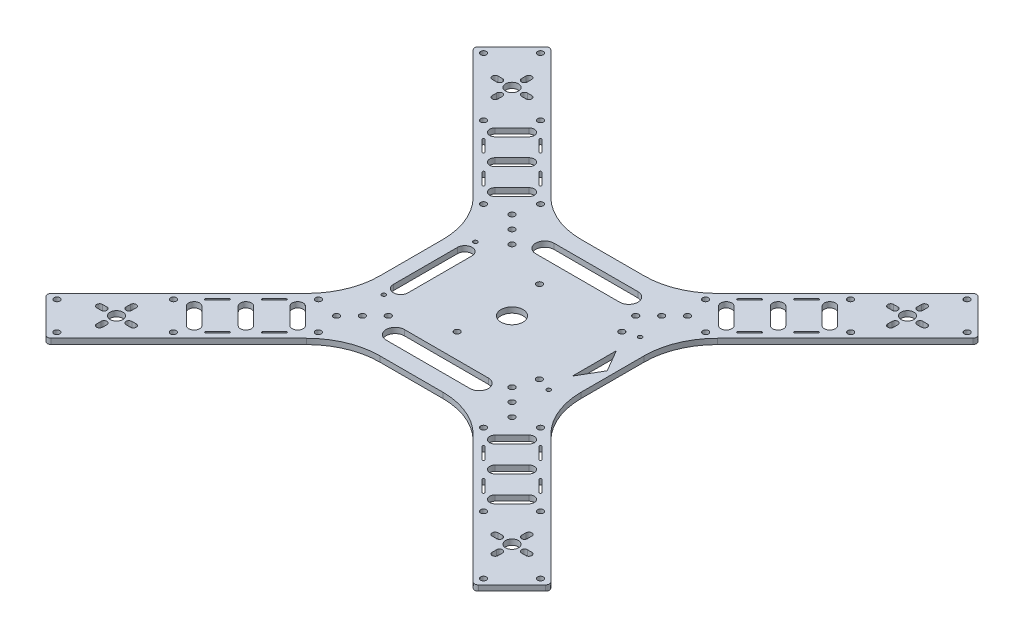
SolidWorks part; units mm, degrees
ref_plane "前视基准面" through (0, 0, 0) normal (0, 0, 1) x (1, 0, 0)
ref_plane "上视基准面" through (0, 0, 0) normal (0, 1, 0) x (1, 0, 0)
ref_plane "右视基准面" through (0, 0, 0) normal (1, 0, 0) x (0, 0, -1)
other "Configuration Table"
sketch "草图1" plane through (0, 0, 0) normal (0, 1, 0) x (1, 0, 0)
  line L0 (-17.2183, 55) -> (17.2183, 55)
  line L1 (-55, 17.2183) -> (-55, -17.2183)
  line L2 (55, 17.2183) -> (55, -17.2183)
  line L3 (-17.2183, -55) -> (17.2183, -55)
  line L4 (0, 55) -> (0, -55) construction
  line L5 (55, 55) -> (-55, -55) construction
  line L6 (45.5025, 66.7157) -> (116.6726, 137.8858)
  line L7 (-137.8858, -116.6726) -> (-116.6726, -137.8858)
  line L8 (116.6726, 137.8858) -> (137.8858, 116.6726)
  line L9 (66.7157, 45.5025) -> (137.8858, 116.6726)
  line L10 (55, 55) -> (108.033, 108.033) construction
  line L11 (55, 55) -> (58.5355, 58.5355)
  line L12 (-116.6726, 137.8858) -> (-45.5025, 66.7157)
  line L13 (-116.6726, 137.8858) -> (-137.8858, 116.6726)
  line L14 (-137.8858, 116.6726) -> (-66.7157, 45.5025)
  line L15 (137.8858, -116.6726) -> (116.6726, -137.8858)
  line L16 (66.7157, -45.5025) -> (137.8858, -116.6726)
  line L17 (116.6726, -137.8858) -> (45.5025, -66.7157)
  line L18 (-137.8858, -116.6726) -> (-66.7157, -45.5025)
  line L19 (-116.6726, -137.8858) -> (-45.5025, -66.7157)
  line L20 (68.0815, 77.2739) -> (77.2739, 68.0815) construction
  line L21 (53.9393, 63.1317) -> (63.1317, 53.9393) construction
  line L22 (70.2028, 79.3952) -> (79.3952, 70.2028)
  line L23 (56.0607, 65.253) -> (65.253, 56.0607)
  line L24 (51.818, 61.0104) -> (61.0104, 51.818)
  line L25 (65.9602, 75.1525) -> (75.1525, 65.9602)
  line L26 (82.2236, 91.416) -> (91.416, 82.2236) construction
  line L27 (84.3449, 93.5373) -> (93.5373, 84.3449)
  line L28 (80.1023, 89.2947) -> (89.2947, 80.1023)
  line L29 (45.1005, 60.6569) -> (84.6985, 100.2548) construction
  line L30 (45.1005, 60.6569) -> (60.6569, 45.1005) construction
  line L31 (84.6985, 100.2548) -> (100.2548, 84.6985) construction
  line L32 (60.6569, 45.1005) -> (100.2548, 84.6985) construction
  line L33 (45.1005, 60.6569) -> (100.2548, 84.6985) construction
  line L34 (84.6985, 100.2548) -> (60.6569, 45.1005) construction
  line L35 (68.0815, 77.2739) -> (77.2739, 68.0815)
  line L36 (108.033, 117.233) -> (108.033, 114.833) construction
  line L37 (117.233, 108.033) -> (114.833, 108.033) construction
  line L38 (109.633, 117.233) -> (109.633, 114.833)
  line L39 (106.433, 117.233) -> (106.433, 114.833)
  line L40 (117.233, 106.433) -> (114.833, 106.433)
  line L41 (117.233, 109.633) -> (114.833, 109.633)
  line L42 (108.033, 98.833) -> (108.033, 101.233) construction
  line L43 (106.433, 98.833) -> (106.433, 101.233)
  line L44 (109.633, 98.833) -> (109.633, 101.233)
  line L45 (98.833, 108.033) -> (101.233, 108.033) construction
  line L46 (98.833, 109.633) -> (101.233, 109.633)
  line L47 (98.833, 106.433) -> (101.233, 106.433)
  line L48 (55, -55) -> (58.5355, -58.5355)
  line L49 (77.2739, -68.0815) -> (68.0815, -77.2739)
  line L50 (55, -55) -> (108.033, -108.033) construction
  line L51 (60.6569, -45.1005) -> (100.2548, -84.6985) construction
  line L52 (60.6569, -45.1005) -> (45.1005, -60.6569) construction
  line L53 (100.2548, -84.6985) -> (84.6985, -100.2548) construction
  line L54 (45.1005, -60.6569) -> (84.6985, -100.2548) construction
  line L55 (60.6569, -45.1005) -> (84.6985, -100.2548) construction
  line L56 (100.2548, -84.6985) -> (45.1005, -60.6569) construction
  line L57 (63.1317, -53.9393) -> (53.9393, -63.1317) construction
  line L58 (65.253, -56.0607) -> (56.0607, -65.253)
  line L59 (61.0104, -51.818) -> (51.818, -61.0104)
  line L60 (77.2739, -68.0815) -> (68.0815, -77.2739) construction
  line L61 (79.3952, -70.2028) -> (70.2028, -79.3952)
  line L62 (75.1525, -65.9602) -> (65.9602, -75.1525)
  line L63 (91.416, -82.2236) -> (82.2236, -91.416) construction
  line L64 (93.5373, -84.3449) -> (84.3449, -93.5373)
  line L65 (89.2947, -80.1023) -> (80.1023, -89.2947)
  line L66 (117.233, -108.033) -> (114.833, -108.033) construction
  line L67 (117.233, -109.633) -> (114.833, -109.633)
  line L68 (117.233, -106.433) -> (114.833, -106.433)
  line L69 (108.033, -117.233) -> (108.033, -114.833) construction
  line L70 (106.433, -117.233) -> (106.433, -114.833)
  line L71 (109.633, -117.233) -> (109.633, -114.833)
  line L72 (98.833, -108.033) -> (101.233, -108.033) construction
  line L73 (98.833, -106.433) -> (101.233, -106.433)
  line L74 (98.833, -109.633) -> (101.233, -109.633)
  line L75 (108.033, -98.833) -> (108.033, -101.233) construction
  line L76 (109.633, -98.833) -> (109.633, -101.233)
  line L77 (106.433, -98.833) -> (106.433, -101.233)
  line L78 (-55, -55) -> (-58.5355, -58.5355)
  line L79 (-68.0815, -77.2739) -> (-77.2739, -68.0815)
  line L80 (-55, -55) -> (-108.033, -108.033) construction
  line L81 (-45.1005, -60.6569) -> (-84.6985, -100.2548) construction
  line L82 (-45.1005, -60.6569) -> (-60.6569, -45.1005) construction
  line L83 (-84.6985, -100.2548) -> (-100.2548, -84.6985) construction
  line L84 (-60.6569, -45.1005) -> (-100.2548, -84.6985) construction
  line L85 (-45.1005, -60.6569) -> (-100.2548, -84.6985) construction
  line L86 (-84.6985, -100.2548) -> (-60.6569, -45.1005) construction
  line L87 (-53.9393, -63.1317) -> (-63.1317, -53.9393) construction
  line L88 (-56.0607, -65.253) -> (-65.253, -56.0607)
  line L89 (-51.818, -61.0104) -> (-61.0104, -51.818)
  line L90 (-68.0815, -77.2739) -> (-77.2739, -68.0815) construction
  line L91 (-70.2028, -79.3952) -> (-79.3952, -70.2028)
  line L92 (-65.9602, -75.1525) -> (-75.1525, -65.9602)
  line L93 (-82.2236, -91.416) -> (-91.416, -82.2236) construction
  line L94 (-84.3449, -93.5373) -> (-93.5373, -84.3449)
  line L95 (-80.1023, -89.2947) -> (-89.2947, -80.1023)
  line L96 (-108.033, -117.233) -> (-108.033, -114.833) construction
  line L97 (-109.633, -117.233) -> (-109.633, -114.833)
  line L98 (-106.433, -117.233) -> (-106.433, -114.833)
  line L99 (-117.233, -108.033) -> (-114.833, -108.033) construction
  line L100 (-117.233, -106.433) -> (-114.833, -106.433)
  line L101 (-117.233, -109.633) -> (-114.833, -109.633)
  line L102 (-108.033, -98.833) -> (-108.033, -101.233) construction
  line L103 (-106.433, -98.833) -> (-106.433, -101.233)
  line L104 (-109.633, -98.833) -> (-109.633, -101.233)
  line L105 (-98.833, -108.033) -> (-101.233, -108.033) construction
  line L106 (-98.833, -109.633) -> (-101.233, -109.633)
  line L107 (-98.833, -106.433) -> (-101.233, -106.433)
  line L108 (-55, 55) -> (-58.5355, 58.5355)
  line L109 (-77.2739, 68.0815) -> (-68.0815, 77.2739)
  line L110 (-55, 55) -> (-108.033, 108.033) construction
  line L111 (-60.6569, 45.1005) -> (-100.2548, 84.6985) construction
  line L112 (-60.6569, 45.1005) -> (-45.1005, 60.6569) construction
  line L113 (-100.2548, 84.6985) -> (-84.6985, 100.2548) construction
  line L114 (-45.1005, 60.6569) -> (-84.6985, 100.2548) construction
  line L115 (-60.6569, 45.1005) -> (-84.6985, 100.2548) construction
  line L116 (-100.2548, 84.6985) -> (-45.1005, 60.6569) construction
  line L117 (-63.1317, 53.9393) -> (-53.9393, 63.1317) construction
  line L118 (-65.253, 56.0607) -> (-56.0607, 65.253)
  line L119 (-61.0104, 51.818) -> (-51.818, 61.0104)
  line L120 (-77.2739, 68.0815) -> (-68.0815, 77.2739) construction
  line L121 (-79.3952, 70.2028) -> (-70.2028, 79.3952)
  line L122 (-75.1525, 65.9602) -> (-65.9602, 75.1525)
  line L123 (-91.416, 82.2236) -> (-82.2236, 91.416) construction
  line L124 (-93.5373, 84.3449) -> (-84.3449, 93.5373)
  line L125 (-89.2947, 80.1023) -> (-80.1023, 89.2947)
  line L126 (-117.233, 108.033) -> (-114.833, 108.033) construction
  line L127 (-117.233, 109.633) -> (-114.833, 109.633)
  line L128 (-117.233, 106.433) -> (-114.833, 106.433)
  line L129 (-108.033, 117.233) -> (-108.033, 114.833) construction
  line L130 (-106.433, 117.233) -> (-106.433, 114.833)
  line L131 (-109.633, 117.233) -> (-109.633, 114.833)
  line L132 (-98.833, 108.033) -> (-101.233, 108.033) construction
  line L133 (-98.833, 106.433) -> (-101.233, 106.433)
  line L134 (-98.833, 109.633) -> (-101.233, 109.633)
  line L135 (-108.033, 98.833) -> (-108.033, 101.233) construction
  line L136 (-109.633, 98.833) -> (-109.633, 101.233)
  line L137 (-106.433, 98.833) -> (-106.433, 101.233)
  line L142 (-25.2933, 0) -> (25.2933, 0) construction
  line L143 (72.3283, 21.6796) -> (-80.2594, -24.0569) construction
  line L144 (-45, 25) -> (45, 25) construction
  line L145 (-45, 25) -> (-45, -25) construction
  line L146 (45, 25) -> (45, -25) construction
  line L147 (-45, -25) -> (45, -25) construction
  line L148 (-45, 25) -> (45, -25) construction
  line L149 (45, 25) -> (-45, -25) construction
  line L150 (55, 55) -> (47.9289, 47.9289)
  line L151 (-47.9289, 47.9289) -> (47.9289, 47.9289)
  line L152 (-40.8579, 40.8579) -> (40.8579, 40.8579)
  line L153 (-33.7868, 33.7868) -> (33.7868, 33.7868)
  line L154 (52, 0) -> (45, 0) construction
  line L155 (30, 47.9289) -> (47.9289, 47.9289) construction
  line L158 (30, 47.9289) -> (15.8579, 33.7868) construction
  line L159 (47.9289, 47.9289) -> (33.7868, 33.7868) construction
  line L160 (15.8579, 33.7868) -> (33.7868, 33.7868) construction
  line L161 (-22.9289, 40.8579) -> (22.9289, 40.8579) construction
  line L162 (-22.9289, 45.8579) -> (22.9289, 45.8579)
  line L163 (-22.9289, 35.8579) -> (22.9289, 35.8579)
  line L164 (45, 0) -> (45, 12)
  line L167 (45, 12) -> (52, 0)
  line L170 (-22.9289, -40.8579) -> (22.9289, -40.8579) construction
  line L171 (-22.9289, -45.8579) -> (22.9289, -45.8579)
  line L172 (-22.9289, -35.8579) -> (22.9289, -35.8579)
  line L173 (45, 0) -> (45, -12)
  line L176 (25.2933, 0) -> (52, 0) construction
  line L180 (-25.2933, 0) -> (-43.2933, 0)
  line L181 (-43.2933, 17.5) -> (-43.2933, -17.5) construction
  line L182 (69.4957, 53.9393) -> (75.8597, 60.3033) construction
  line L183 (-39.2933, 17.5) -> (-39.2933, -17.5)
  line L184 (-47.2933, 17.5) -> (-47.2933, -17.5)
  line L185 (85.052, 69.4957) -> (91.416, 75.8597) construction
  line L186 (69.1421, 54.2929) -> (75.5061, 60.6569)
  line L187 (69.8492, 53.5858) -> (76.2132, 59.9497)
  line L188 (84.6985, 69.8492) -> (91.0624, 76.2132)
  line L189 (85.4056, 69.1421) -> (91.7696, 75.5061)
  line L190 (53.9393, 69.4957) -> (60.3033, 75.8597) construction
  line L191 (54.2929, 69.1421) -> (60.6569, 75.5061)
  line L192 (53.5858, 69.8492) -> (59.9497, 76.2132)
  line L193 (69.4957, 85.052) -> (75.8597, 91.416) construction
  line L194 (69.8492, 84.6985) -> (76.2132, 91.0624)
  line L195 (69.1421, 85.4056) -> (75.5061, 91.7696)
  line L196 (53.9393, -69.4957) -> (60.3033, -75.8597) construction
  line L197 (54.2929, -69.1421) -> (60.6569, -75.5061)
  line L198 (53.5858, -69.8492) -> (59.9497, -76.2132)
  line L199 (69.4957, -85.052) -> (75.8597, -91.416) construction
  line L200 (69.8492, -84.6985) -> (76.2132, -91.0624)
  line L201 (69.1421, -85.4056) -> (75.5061, -91.7696)
  line L202 (69.4957, -53.9393) -> (75.8597, -60.3033) construction
  line L203 (69.1421, -54.2929) -> (75.5061, -60.6569)
  line L204 (69.8492, -53.5858) -> (76.2132, -59.9497)
  line L205 (85.052, -69.4957) -> (91.416, -75.8597) construction
  line L206 (84.6985, -69.8492) -> (91.0624, -76.2132)
  line L207 (85.4056, -69.1421) -> (91.7696, -75.5061)
  line L208 (-69.4957, -53.9393) -> (-75.8597, -60.3033) construction
  line L209 (-69.1421, -54.2929) -> (-75.5061, -60.6569)
  line L210 (-69.8492, -53.5858) -> (-76.2132, -59.9497)
  line L211 (-85.052, -69.4957) -> (-91.416, -75.8597) construction
  line L212 (-84.6985, -69.8492) -> (-91.0624, -76.2132)
  line L213 (-85.4056, -69.1421) -> (-91.7696, -75.5061)
  line L214 (-53.9393, -69.4957) -> (-60.3033, -75.8597) construction
  line L215 (-54.2929, -69.1421) -> (-60.6569, -75.5061)
  line L216 (-53.5858, -69.8492) -> (-59.9497, -76.2132)
  line L217 (-69.4957, -85.052) -> (-75.8597, -91.416) construction
  line L218 (-69.8492, -84.6985) -> (-76.2132, -91.0624)
  line L219 (-69.1421, -85.4056) -> (-75.5061, -91.7696)
  line L220 (-53.9393, 69.4957) -> (-60.3033, 75.8597) construction
  line L221 (-54.2929, 69.1421) -> (-60.6569, 75.5061)
  line L222 (-53.5858, 69.8492) -> (-59.9497, 76.2132)
  line L223 (-69.4957, 85.052) -> (-75.8597, 91.416) construction
  line L224 (-69.8492, 84.6985) -> (-76.2132, 91.0624)
  line L225 (-69.1421, 85.4056) -> (-75.5061, 91.7696)
  line L226 (-69.4957, 53.9393) -> (-75.8597, 60.3033) construction
  line L227 (-69.1421, 54.2929) -> (-75.5061, 60.6569)
  line L228 (-69.8492, 53.5858) -> (-76.2132, 59.9497)
  line L229 (-85.052, 69.4957) -> (-91.416, 75.8597) construction
  line L230 (-84.6985, 69.8492) -> (-91.0624, 76.2132)
  line L231 (-85.4056, 69.1421) -> (-91.7696, 75.5061)
  line L232 (45, -12) -> (52, 0)
  line L233 (0, 0) -> (15, 0)
  line L234 (-7.5, 22.5) -> (37.5, 22.5) construction
  line L235 (-7.5, 22.5) -> (-7.5, -22.5) construction
  line L236 (37.5, 22.5) -> (37.5, -22.5) construction
  line L237 (-7.5, -22.5) -> (37.5, -22.5) construction
  line L238 (-7.5, 22.5) -> (37.5, -22.5) construction
  line L239 (37.5, 22.5) -> (-7.5, -22.5) construction
  arc A0 (-55, 17.2183) -> (-66.7157, 45.5025) centre (-95, 17.2183) ccw
  arc A1 (55, 17.2183) -> (66.7157, 45.5025) centre (95, 17.2183) cw
  arc A2 (45.5025, 66.7157) -> (17.2183, 55) centre (17.2183, 95) cw
  arc A3 (-17.2183, 55) -> (-45.5025, 66.7157) centre (-17.2183, 95) cw
  arc A4 (66.7157, -45.5025) -> (55, -17.2183) centre (95, -17.2183) cw
  arc A5 (17.2183, -55) -> (45.5025, -66.7157) centre (17.2183, -95) cw
  arc A6 (-17.2183, -55) -> (-45.5025, -66.7157) centre (-17.2183, -95) ccw
  arc A7 (-66.7157, -45.5025) -> (-55, -17.2183) centre (-95, -17.2183) ccw
  circle A8 centre (108.033, 108.033) radius 14 construction
  circle A9 centre (108.033, 108.033) radius 8 construction
  circle A12 centre (116.033, 108.033) radius 1.6 construction
  circle A13 centre (108.033, 100.033) radius 1.6 construction
  circle A14 centre (100.033, 108.033) radius 1.6 construction
  circle A15 centre (108.033, 116.033) radius 1.6 construction
  arc A16 (56.0607, 65.253) -> (51.818, 61.0104) centre (53.9393, 63.1317) ccw
  arc A17 (61.0104, 51.818) -> (65.253, 56.0607) centre (63.1317, 53.9393) ccw
  arc A18 (70.2028, 79.3952) -> (65.9602, 75.1525) centre (68.0815, 77.2739) ccw
  arc A19 (75.1525, 65.9602) -> (79.3952, 70.2028) centre (77.2739, 68.0815) ccw
  arc A20 (84.3449, 93.5373) -> (80.1023, 89.2947) centre (82.2236, 91.416) ccw
  arc A21 (89.2947, 80.1023) -> (93.5373, 84.3449) centre (91.416, 82.2236) ccw
  circle A22 centre (84.6985, 100.2548) radius 1.6
  circle A23 centre (100.2548, 84.6985) radius 1.6
  circle A24 centre (60.6569, 45.1005) radius 1.6
  circle A25 centre (45.1005, 60.6569) radius 1.6
  circle A26 centre (108.033, 108.033) radius 3.5
  arc A27 (109.633, 117.233) -> (106.433, 117.233) centre (108.033, 117.233) ccw
  arc A28 (106.433, 114.833) -> (109.633, 114.833) centre (108.033, 114.833) ccw
  arc A29 (117.233, 106.433) -> (117.233, 109.633) centre (117.233, 108.033) ccw
  arc A30 (114.833, 109.633) -> (114.833, 106.433) centre (114.833, 108.033) ccw
  arc A31 (106.433, 98.833) -> (109.633, 98.833) centre (108.033, 98.833) ccw
  arc A32 (109.633, 101.233) -> (106.433, 101.233) centre (108.033, 101.233) ccw
  arc A33 (98.833, 109.633) -> (98.833, 106.433) centre (98.833, 108.033) ccw
  arc A34 (101.233, 106.433) -> (101.233, 109.633) centre (101.233, 108.033) ccw
  circle A35 centre (116.5183, 132.0746) radius 1.6
  circle A36 centre (132.0746, 116.5183) radius 1.6
  circle A37 centre (100.2548, -84.6985) radius 1.6
  circle A38 centre (84.6985, -100.2548) radius 1.6
  circle A39 centre (45.1005, -60.6569) radius 1.6
  circle A40 centre (60.6569, -45.1005) radius 1.6
  circle A41 centre (108.033, -108.033) radius 3.5
  circle A42 centre (132.0746, -116.5183) radius 1.6
  circle A43 centre (116.5183, -132.0746) radius 1.6
  circle A44 centre (108.033, -108.033) radius 14 construction
  circle A45 centre (108.033, -108.033) radius 8 construction
  circle A46 centre (108.033, -116.033) radius 1.6 construction
  circle A47 centre (100.033, -108.033) radius 1.6 construction
  circle A48 centre (108.033, -100.033) radius 1.6 construction
  circle A49 centre (116.033, -108.033) radius 1.6 construction
  arc A50 (65.253, -56.0607) -> (61.0104, -51.818) centre (63.1317, -53.9393) ccw
  arc A51 (51.818, -61.0104) -> (56.0607, -65.253) centre (53.9393, -63.1317) ccw
  arc A52 (79.3952, -70.2028) -> (75.1525, -65.9602) centre (77.2739, -68.0815) ccw
  arc A53 (65.9602, -75.1525) -> (70.2028, -79.3952) centre (68.0815, -77.2739) ccw
  arc A54 (93.5373, -84.3449) -> (89.2947, -80.1023) centre (91.416, -82.2236) ccw
  arc A55 (80.1023, -89.2947) -> (84.3449, -93.5373) centre (82.2236, -91.416) ccw
  arc A56 (117.233, -109.633) -> (117.233, -106.433) centre (117.233, -108.033) ccw
  arc A57 (114.833, -106.433) -> (114.833, -109.633) centre (114.833, -108.033) ccw
  arc A58 (106.433, -117.233) -> (109.633, -117.233) centre (108.033, -117.233) ccw
  arc A59 (109.633, -114.833) -> (106.433, -114.833) centre (108.033, -114.833) ccw
  arc A60 (98.833, -106.433) -> (98.833, -109.633) centre (98.833, -108.033) ccw
  arc A61 (101.233, -109.633) -> (101.233, -106.433) centre (101.233, -108.033) ccw
  arc A62 (109.633, -98.833) -> (106.433, -98.833) centre (108.033, -98.833) ccw
  arc A63 (106.433, -101.233) -> (109.633, -101.233) centre (108.033, -101.233) ccw
  circle A64 centre (-84.6985, -100.2548) radius 1.6
  circle A65 centre (-100.2548, -84.6985) radius 1.6
  circle A66 centre (-60.6569, -45.1005) radius 1.6
  circle A67 centre (-45.1005, -60.6569) radius 1.6
  circle A68 centre (-108.033, -108.033) radius 3.5
  circle A69 centre (-116.5183, -132.0746) radius 1.6
  circle A70 centre (-132.0746, -116.5183) radius 1.6
  circle A71 centre (-108.033, -108.033) radius 14 construction
  circle A72 centre (-108.033, -108.033) radius 8 construction
  circle A73 centre (-116.033, -108.033) radius 1.6 construction
  circle A74 centre (-108.033, -100.033) radius 1.6 construction
  circle A75 centre (-100.033, -108.033) radius 1.6 construction
  circle A76 centre (-108.033, -116.033) radius 1.6 construction
  arc A77 (-56.0607, -65.253) -> (-51.818, -61.0104) centre (-53.9393, -63.1317) ccw
  arc A78 (-61.0104, -51.818) -> (-65.253, -56.0607) centre (-63.1317, -53.9393) ccw
  arc A79 (-70.2028, -79.3952) -> (-65.9602, -75.1525) centre (-68.0815, -77.2739) ccw
  arc A80 (-75.1525, -65.9602) -> (-79.3952, -70.2028) centre (-77.2739, -68.0815) ccw
  arc A81 (-84.3449, -93.5373) -> (-80.1023, -89.2947) centre (-82.2236, -91.416) ccw
  arc A82 (-89.2947, -80.1023) -> (-93.5373, -84.3449) centre (-91.416, -82.2236) ccw
  arc A83 (-109.633, -117.233) -> (-106.433, -117.233) centre (-108.033, -117.233) ccw
  arc A84 (-106.433, -114.833) -> (-109.633, -114.833) centre (-108.033, -114.833) ccw
  arc A85 (-117.233, -106.433) -> (-117.233, -109.633) centre (-117.233, -108.033) ccw
  arc A86 (-114.833, -109.633) -> (-114.833, -106.433) centre (-114.833, -108.033) ccw
  arc A87 (-106.433, -98.833) -> (-109.633, -98.833) centre (-108.033, -98.833) ccw
  arc A88 (-109.633, -101.233) -> (-106.433, -101.233) centre (-108.033, -101.233) ccw
  arc A89 (-98.833, -109.633) -> (-98.833, -106.433) centre (-98.833, -108.033) ccw
  arc A90 (-101.233, -106.433) -> (-101.233, -109.633) centre (-101.233, -108.033) ccw
  circle A91 centre (-100.2548, 84.6985) radius 1.6
  circle A92 centre (-84.6985, 100.2548) radius 1.6
  circle A93 centre (-45.1005, 60.6569) radius 1.6
  circle A94 centre (-60.6569, 45.1005) radius 1.6
  circle A95 centre (-108.033, 108.033) radius 3.5
  circle A96 centre (-132.0746, 116.5183) radius 1.6
  circle A97 centre (-116.5183, 132.0746) radius 1.6
  circle A98 centre (-108.033, 108.033) radius 14 construction
  circle A99 centre (-108.033, 108.033) radius 8 construction
  circle A100 centre (-108.033, 116.033) radius 1.6 construction
  circle A101 centre (-100.033, 108.033) radius 1.6 construction
  circle A102 centre (-108.033, 100.033) radius 1.6 construction
  circle A103 centre (-116.033, 108.033) radius 1.6 construction
  arc A104 (-65.253, 56.0607) -> (-61.0104, 51.818) centre (-63.1317, 53.9393) ccw
  arc A105 (-51.818, 61.0104) -> (-56.0607, 65.253) centre (-53.9393, 63.1317) ccw
  arc A106 (-79.3952, 70.2028) -> (-75.1525, 65.9602) centre (-77.2739, 68.0815) ccw
  arc A107 (-65.9602, 75.1525) -> (-70.2028, 79.3952) centre (-68.0815, 77.2739) ccw
  arc A108 (-93.5373, 84.3449) -> (-89.2947, 80.1023) centre (-91.416, 82.2236) ccw
  arc A109 (-80.1023, 89.2947) -> (-84.3449, 93.5373) centre (-82.2236, 91.416) ccw
  arc A110 (-117.233, 109.633) -> (-117.233, 106.433) centre (-117.233, 108.033) ccw
  arc A111 (-114.833, 106.433) -> (-114.833, 109.633) centre (-114.833, 108.033) ccw
  arc A112 (-106.433, 117.233) -> (-109.633, 117.233) centre (-108.033, 117.233) ccw
  arc A113 (-109.633, 114.833) -> (-106.433, 114.833) centre (-108.033, 114.833) ccw
  arc A114 (-98.833, 106.433) -> (-98.833, 109.633) centre (-98.833, 108.033) ccw
  arc A115 (-101.233, 109.633) -> (-101.233, 106.433) centre (-101.233, 108.033) ccw
  arc A116 (-109.633, 98.833) -> (-106.433, 98.833) centre (-108.033, 98.833) ccw
  arc A117 (-106.433, 101.233) -> (-109.633, 101.233) centre (-108.033, 101.233) ccw
  circle A118 centre (47.9289, 47.9289) radius 1.6
  circle A119 centre (40.8579, 40.8579) radius 1.6
  circle A120 centre (33.7868, 33.7868) radius 1.6
  circle A121 centre (47.9289, -47.9289) radius 1.6
  circle A122 centre (40.8579, -40.8579) radius 1.6
  circle A123 centre (33.7868, -33.7868) radius 1.6
  circle A124 centre (-47.9289, -47.9289) radius 1.6
  circle A125 centre (-40.8579, -40.8579) radius 1.6
  circle A126 centre (-33.7868, -33.7868) radius 1.6
  circle A127 centre (-47.9289, 47.9289) radius 1.6
  circle A128 centre (-40.8579, 40.8579) radius 1.6
  circle A129 centre (-33.7868, 33.7868) radius 1.6
  arc A132 (-22.9289, 45.8579) -> (-22.9289, 35.8579) centre (-22.9289, 40.8579) ccw
  arc A133 (22.9289, 35.8579) -> (22.9289, 45.8579) centre (22.9289, 40.8579) ccw
  arc A138 (-22.9289, -45.8579) -> (-22.9289, -35.8579) centre (-22.9289, -40.8579) cw
  arc A139 (22.9289, -35.8579) -> (22.9289, -45.8579) centre (22.9289, -40.8579) cw
  arc A142 (-39.2933, 17.5) -> (-47.2933, 17.5) centre (-43.2933, 17.5) ccw
  arc A143 (-47.2933, -17.5) -> (-39.2933, -17.5) centre (-43.2933, -17.5) ccw
  arc A144 (69.1421, 54.2929) -> (69.8492, 53.5858) centre (69.4957, 53.9393) ccw
  arc A145 (76.2132, 59.9497) -> (75.5061, 60.6569) centre (75.8597, 60.3033) ccw
  arc A146 (84.6985, 69.8492) -> (85.4056, 69.1421) centre (85.052, 69.4957) ccw
  arc A147 (91.7696, 75.5061) -> (91.0624, 76.2132) centre (91.416, 75.8597) ccw
  arc A148 (54.2929, 69.1421) -> (53.5858, 69.8492) centre (53.9393, 69.4957) cw
  arc A149 (59.9497, 76.2132) -> (60.6569, 75.5061) centre (60.3033, 75.8597) cw
  arc A150 (69.8492, 84.6985) -> (69.1421, 85.4056) centre (69.4957, 85.052) cw
  arc A151 (75.5061, 91.7696) -> (76.2132, 91.0624) centre (75.8597, 91.416) cw
  arc A152 (54.2929, -69.1421) -> (53.5858, -69.8492) centre (53.9393, -69.4957) ccw
  arc A153 (59.9497, -76.2132) -> (60.6569, -75.5061) centre (60.3033, -75.8597) ccw
  arc A154 (69.8492, -84.6985) -> (69.1421, -85.4056) centre (69.4957, -85.052) ccw
  arc A155 (75.5061, -91.7696) -> (76.2132, -91.0624) centre (75.8597, -91.416) ccw
  arc A156 (69.1421, -54.2929) -> (69.8492, -53.5858) centre (69.4957, -53.9393) cw
  arc A157 (76.2132, -59.9497) -> (75.5061, -60.6569) centre (75.8597, -60.3033) cw
  arc A158 (84.6985, -69.8492) -> (85.4056, -69.1421) centre (85.052, -69.4957) cw
  arc A159 (91.7696, -75.5061) -> (91.0624, -76.2132) centre (91.416, -75.8597) cw
  arc A160 (-69.1421, -54.2929) -> (-69.8492, -53.5858) centre (-69.4957, -53.9393) ccw
  arc A161 (-76.2132, -59.9497) -> (-75.5061, -60.6569) centre (-75.8597, -60.3033) ccw
  arc A162 (-84.6985, -69.8492) -> (-85.4056, -69.1421) centre (-85.052, -69.4957) ccw
  arc A163 (-91.7696, -75.5061) -> (-91.0624, -76.2132) centre (-91.416, -75.8597) ccw
  arc A164 (-54.2929, -69.1421) -> (-53.5858, -69.8492) centre (-53.9393, -69.4957) cw
  arc A165 (-59.9497, -76.2132) -> (-60.6569, -75.5061) centre (-60.3033, -75.8597) cw
  arc A166 (-69.8492, -84.6985) -> (-69.1421, -85.4056) centre (-69.4957, -85.052) cw
  arc A167 (-75.5061, -91.7696) -> (-76.2132, -91.0624) centre (-75.8597, -91.416) cw
  arc A168 (-54.2929, 69.1421) -> (-53.5858, 69.8492) centre (-53.9393, 69.4957) ccw
  arc A169 (-59.9497, 76.2132) -> (-60.6569, 75.5061) centre (-60.3033, 75.8597) ccw
  arc A170 (-69.8492, 84.6985) -> (-69.1421, 85.4056) centre (-69.4957, 85.052) ccw
  arc A171 (-75.5061, 91.7696) -> (-76.2132, 91.0624) centre (-75.8597, 91.416) ccw
  arc A172 (-69.1421, 54.2929) -> (-69.8492, 53.5858) centre (-69.4957, 53.9393) cw
  arc A173 (-76.2132, 59.9497) -> (-75.5061, 60.6569) centre (-75.8597, 60.3033) cw
  arc A174 (-84.6985, 69.8492) -> (-85.4056, 69.1421) centre (-85.052, 69.4957) cw
  arc A175 (-91.7696, 75.5061) -> (-91.0624, 76.2132) centre (-91.416, 75.8597) cw
  circle A176 centre (-45, 25) radius 1.1
  circle A177 centre (45, 25) radius 1.1
  circle A178 centre (45, -25) radius 1.1
  circle A179 centre (-45, -25) radius 1.1
  circle A197 centre (0, 0) radius 6
  circle A198 centre (-7.5, 22.5) radius 1.6
  circle A199 centre (37.5, 22.5) radius 1.6
  circle A200 centre (37.5, -22.5) radius 1.6
  circle A201 centre (-7.5, -22.5) radius 1.6
  point P1 (0, 0)
  point P2 (0, 0)
  point P14 (0, 0)
  point P54 (108.033, 108.033)
  point P56 (72.6777, 72.6777)
  point P58 (58.5355, 58.5355)
  point P64 (72.6777, 72.6777)
  point P71 (86.8198, 86.8198)
  point P89 (0, 0)
  point P90 (108.033, 116.033)
  point P98 (116.033, 108.033)
  point P105 (108.033, 100.033)
  point P112 (100.033, 108.033)
  point P117 (108.033, 108.033)
  point P121 (0, 0)
  point P137 (108.033, -108.033)
  point P139 (72.6777, -72.6777)
  point P141 (58.5355, -58.5355)
  point P147 (72.6777, -72.6777)
  point P154 (86.8198, -86.8198)
  point P171 (116.033, -108.033)
  point P179 (108.033, -116.033)
  point P186 (100.033, -108.033)
  point P193 (108.033, -100.033)
  point P198 (108.033, -108.033)
  point P217 (-108.033, -108.033)
  point P219 (-72.6777, -72.6777)
  point P221 (-58.5355, -58.5355)
  point P227 (-72.6777, -72.6777)
  point P234 (-86.8198, -86.8198)
  point P251 (-108.033, -116.033)
  point P259 (-116.033, -108.033)
  point P266 (-108.033, -100.033)
  point P273 (-100.033, -108.033)
  point P278 (-108.033, -108.033)
  point P297 (-108.033, 108.033)
  point P299 (-72.6777, 72.6777)
  point P301 (-58.5355, 58.5355)
  point P307 (-72.6777, 72.6777)
  point P314 (-86.8198, 86.8198)
  point P331 (-116.033, 108.033)
  point P339 (-108.033, 116.033)
  point P346 (-100.033, 108.033)
  point P353 (-108.033, 100.033)
  point P358 (-108.033, 108.033)
  point P362 (0, 0)
  point P378 (22.9289, 40.8579)
  point P397 (0, 0)
  point P404 (18.2028, 64.3461)
  point P407 (0, 40.8579)
  point P424 (15, 0)
  point P428 (0, -40.8579)
  point P447 (72.6777, 57.1213)
  point P448 (88.234, 72.6777)
  point P449 (-43.2933, 0)
  point P458 (72.6777, 57.1213)
  point P463 (88.234, 72.6777)
  point P470 (57.1213, 72.6777)
  point P477 (72.6777, 88.234)
  point P489 (57.1213, -72.6777)
  point P494 (72.6777, -88.234)
  point P501 (72.6777, -57.1213)
  point P508 (88.234, -72.6777)
  point P517 (-72.6777, -57.1213)
  point P522 (-88.234, -72.6777)
  point P529 (-57.1213, -72.6777)
  point P536 (-72.6777, -88.234)
  point P545 (-57.1213, 72.6777)
  point P550 (-72.6777, 88.234)
  point P557 (-72.6777, 57.1213)
  point P564 (-88.234, 72.6777)
  point P569 (0, 0)
  dimension "D1" = 40
  dimension "D2" = 40
  dimension "D4" = 28
  dimension "D6" = 16
  dimension "D7" = 3.2
  dimension "D8" = 4
  dimension "D10" = 3
  dimension "D13" = 3.2
  dimension "D14" = 7
  dimension "D15" = 4
  dimension "D23" = 3.2
  dimension "D28" = 4
  dimension "D29" = 2.2
  dimension "D30" = 2.2
  dimension "D31" = 2.2
  dimension "D32" = 2.2
  dimension "D37" = 12
  dimension "D38" = 12
  dimension "D26" = 12
  dimension "D42" = 3.2
  dimension "D3" = 75
  dimension "D9" = 5
  dimension "D11" = 56
  dimension "D12" = 22
  dimension "D18" = 100
  dimension "D19" = 60
  dimension "D20" = 90
  dimension "D21" = 50
  dimension "D22" = 10
  dimension "D27" = 18
  dimension "D39" = 15
  dimension "D40" = 45
  dimension "D41" = 45
  dimension "D16" = 2
  dimension "D24" = 3
  dimension "D5" = 2
  dimension "D17" = 4
  dimension "D25" = 4
  dimension "D43" = 4
extrude "凸台-拉伸2" add sketch "草图1" along normal blind 3 contours A7 L18 L7 L19 A6 L3 A5 L17 L15 L16 A4 L2 A1 L9 L8 L6 A2 L0 A3 L12 L13 L14 A0 L1 A171 L225 A170 L224 A169 L222 A168 L221 A163 L213 A162 L212 A161 L210 A160 L209 A155 L201 A154 L200 A153
fillet "圆角1" radius 2 1 edges at (137.8858, 1.5, -116.6726)
fillet "圆角2" radius 2 7 edges at (-116.6726, 1.5, -137.8858) (-137.8858, 1.5, -116.6726) (-137.8858, 1.5, 116.6726) (-116.6726, 1.5, 137.8858) (116.6726, 1.5, 137.8858) (137.8858, 1.5, 116.6726) (116.6726, 1.5, -137.8858)
